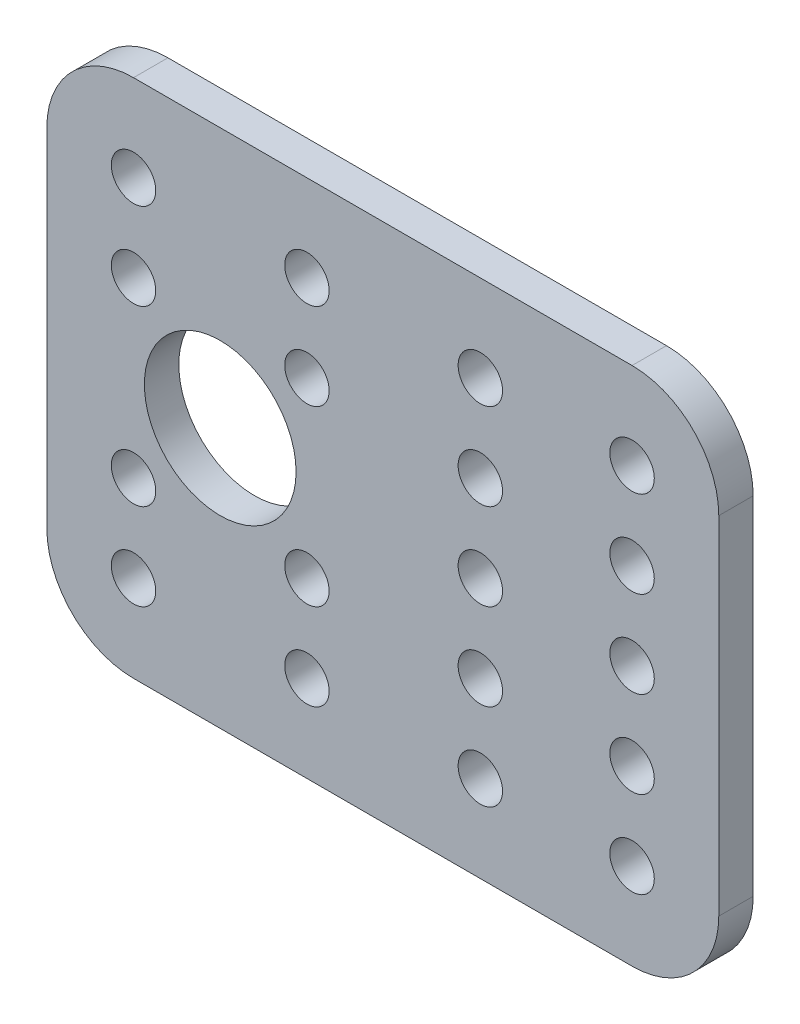
SolidWorks part; units mm, degrees
ref_plane "Front Plane" through (0, 0, 0) normal (0, 0, 1) x (1, 0, 0)
ref_plane "Top Plane" through (0, 0, 0) normal (0, 1, 0) x (1, 0, 0)
ref_plane "Right Plane" through (0, 0, 0) normal (1, 0, 0) x (0, 0, -1)
sketch "Sketch1" plane through (0, 0, 0) normal (0, 0, 1) x (1, 0, 0)
  line L0 (0, 0) -> (-50000, 0) construction
  line L1 (31, -24) -> (-31, -24)
  line L2 (31, -24) -> (31, 24)
  line L3 (31, 24) -> (-31, 24)
  line L4 (-31, -24) -> (-31, 24)
  line L5 (31, -24) -> (-31, 24) construction
  line L6 (31, 24) -> (-31, -24) construction
  line L7 (-23, 8) -> (-7, 8) construction
  line L8 (-23, 8) -> (-23, -8) construction
  line L9 (-23, -8) -> (-7, -8) construction
  line L10 (-7, 8) -> (-7, -8) construction
  line L11 (-23, 8) -> (-7, -8) construction
  line L12 (-23, -8) -> (-7, 8) construction
  line L13 (-23, 16) -> (-7, 16) construction
  line L14 (-31, 24) -> (-23, 24) construction
  line L15 (-31, 24) -> (-31, 16) construction
  line L16 (-31, 16) -> (-23, 16) construction
  line L17 (-23, 24) -> (-23, 16) construction
  line L18 (-23, 16) -> (-23, 8) construction
  line L19 (4.1971, 16) -> (-49994.2793, 16) construction
  circle A0 centre (-15, 0) radius 7
  circle A1 centre (-23, 8) radius 2.05 construction
  circle A2 centre (-7, 8) radius 2.05 construction
  circle A3 centre (-7, -8) radius 2.05 construction
  circle A4 centre (-23, -8) radius 2.05 construction
  circle A5 centre (-23, 16) radius 2.05
  circle A6 centre (-7, 16) radius 2.05
  circle A7 centre (9, 16) radius 2.05
  circle A8 centre (25, 16) radius 2.05 construction
  circle A9 centre (41, 16) radius 2.05 construction
  circle A10 centre (57, 16) radius 2.05 construction
  circle A11 centre (73, 16) radius 2.05 construction
  circle A12 centre (89, 16) radius 2.05 construction
  circle A13 centre (105, 16) radius 2.05 construction
  circle A14 centre (-7, 8) radius 2.05
  circle A15 centre (9, 8) radius 2.05
  circle A16 centre (25, 8) radius 2.05 construction
  circle A17 centre (41, 8) radius 2.05 construction
  circle A18 centre (57, 8) radius 2.05 construction
  circle A19 centre (73, 8) radius 2.05 construction
  circle A20 centre (89, 8) radius 2.05 construction
  circle A21 centre (105, 8) radius 2.05 construction
  circle A22 centre (-7, 0) radius 2.05 construction
  circle A23 centre (9, 0) radius 2.05
  circle A24 centre (25, 0) radius 2.05 construction
  circle A25 centre (41, 0) radius 2.05 construction
  circle A26 centre (57, 0) radius 2.05 construction
  circle A27 centre (73, 0) radius 2.05 construction
  circle A28 centre (89, 0) radius 2.05 construction
  circle A29 centre (105, 0) radius 2.05 construction
  circle A30 centre (-7, -8) radius 2.05
  circle A31 centre (9, -8) radius 2.05
  circle A32 centre (25, -8) radius 2.05 construction
  circle A33 centre (41, -8) radius 2.05 construction
  circle A34 centre (57, -8) radius 2.05 construction
  circle A35 centre (73, -8) radius 2.05 construction
  circle A36 centre (89, -8) radius 2.05 construction
  circle A37 centre (105, -8) radius 2.05 construction
  circle A38 centre (-7, -16) radius 2.05
  circle A39 centre (9, -16) radius 2.05
  circle A40 centre (25, -16) radius 2.05 construction
  circle A41 centre (41, -16) radius 2.05 construction
  circle A42 centre (57, -16) radius 2.05 construction
  circle A43 centre (73, -16) radius 2.05 construction
  circle A44 centre (89, -16) radius 2.05 construction
  circle A45 centre (105, -16) radius 2.05 construction
  circle A46 centre (-23, 8) radius 2.05
  circle A47 centre (-23, 0) radius 2.05 construction
  circle A48 centre (-23, -8) radius 2.05
  circle A49 centre (-23, -16) radius 2.05
  circle A50 centre (23, 16) radius 2.05
  circle A51 centre (23, 8) radius 2.05
  circle A52 centre (23, 0) radius 2.05
  circle A53 centre (23, -8) radius 2.05
  circle A54 centre (23, -16) radius 2.05
  point P0 (0, 0)
  point P6 (-15, 0)
  dimension "D5" = 4.1
  dimension "D6" = 14
  dimension "D13" = 4.1
  dimension "D1" = 48
  dimension "D2" = 62
  dimension "D3" = 16
  dimension "D4" = 8
  dimension "D7" = 8
  dimension "D8" = 8
  dimension "D11" = 16
  dimension "D12" = 8
  dimension "D14" = 8
  dimension "D9" = 9
  dimension "D10" = 5
  dimension "D15" = 5
extrude "Boss-Extrude1" add sketch "Sketch1" along normal blind 3.175
fillet "Fillet1" radius 8 4 edges at (31, 24, 1.5875) (31, -24, 1.5875) (-31, -24, 1.5875) (-31, 24, 1.5875)
